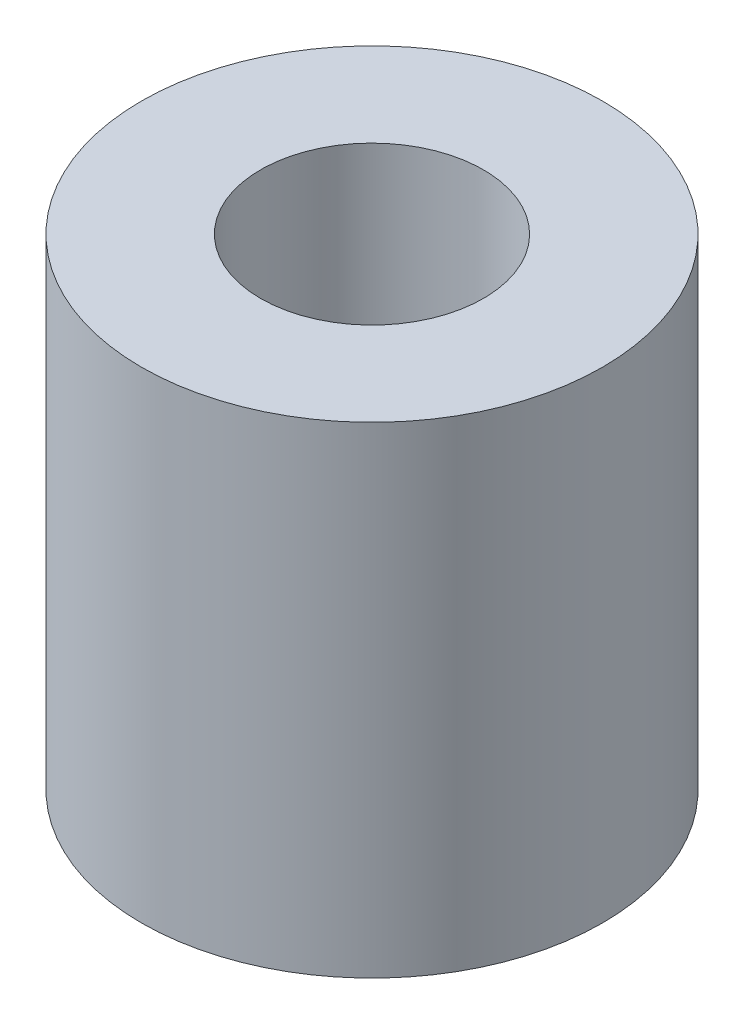
SolidWorks part; units mm, degrees
ref_plane "前视基准面" through (0, 0, 0) normal (0, 0, 1) x (1, 0, 0)
ref_plane "上视基准面" through (0, 0, 0) normal (0, 1, 0) x (1, 0, 0)
ref_plane "右视基准面" through (0, 0, 0) normal (1, 0, 0) x (0, 0, -1)
other "Configuration Table"
sketch "草图1" plane through (0, 0, 0) normal (0, 1, 0) x (1, 0, 0)
  circle A0 centre (0, 0) radius 4.55
  circle A1 centre (0, 0) radius 2.2
  dimension "D1" = 9.1
  dimension "D2" = 4.4
extrude "凸台-拉伸1" add sketch "草图1" along normal blind 9.5
